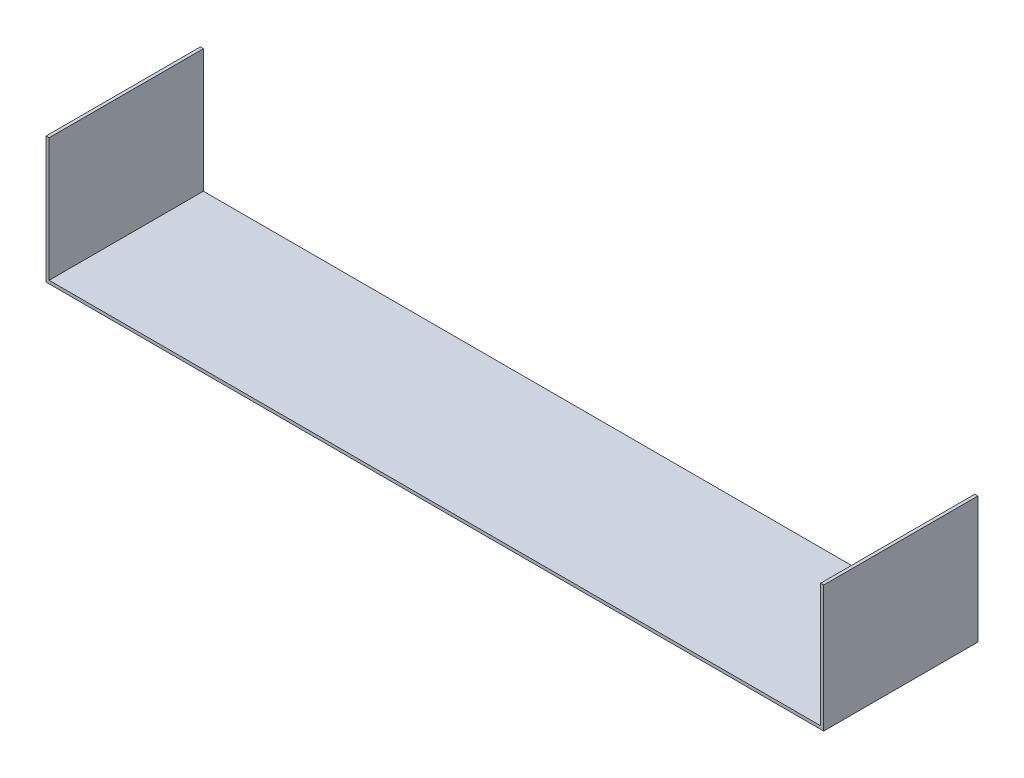
SolidWorks part; units mm, degrees
ref_plane "Front Plane" through (0, 0, 0) normal (0, 0, 1) x (1, 0, 0)
ref_plane "Top Plane" through (0, 0, 0) normal (0, 1, 0) x (1, 0, 0)
ref_plane "Right Plane" through (0, 0, 0) normal (1, 0, 0) x (0, 0, -1)
sketch "Sketch2" plane through (0, 0, 0) normal (0, 0, 1) x (1, 0, 0)
  line L0 (0, 0) -> (0, -8000)
  line L1 (0, -8000) -> (50000, -8000)
  line L2 (50000, -8000) -> (50000, 0)
  line L3 (-200, 0) -> (-200, -8200)
  line L4 (-200, -8200) -> (50200, -8200)
  line L5 (50200, -8200) -> (50200, 0)
  line L6 (-200, 0) -> (0, 0)
  line L7 (50000, 0) -> (50200, 0)
extrude "Boss-Extrude1" add sketch "Sketch2" against normal blind 10000
